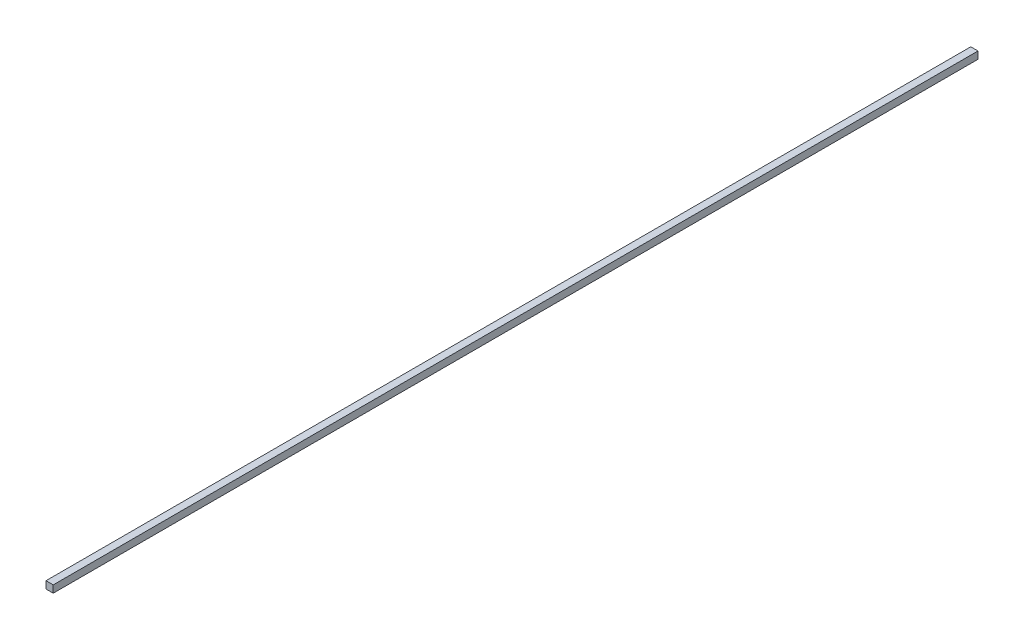
SolidWorks part; units mm, degrees
ref_plane "Front Plane" through (0, 0, 0) normal (0, 0, 1) x (1, 0, 0)
ref_plane "Top Plane" through (0, 0, 0) normal (0, 1, 0) x (1, 0, 0)
ref_plane "Right Plane" through (0, 0, 0) normal (1, 0, 0) x (0, 0, -1)
sketch "Sketch1" plane through (0, 0, 0) normal (0, 0, 1) x (1, 0, 0)
  line L0 (-1.1906, 1.1906) -> (1.1906, -1.1906) construction
  line L1 (-1.1906, 1.1906) -> (1.1906, 1.1906)
  line L2 (-1.1906, 1.1906) -> (-1.1906, -1.1906)
  line L3 (-1.1906, -1.1906) -> (1.1906, -1.1906)
  line L4 (1.1906, 1.1906) -> (1.1906, -1.1906)
  dimension "D1" = 2.3813
  dimension "D2" = 2.3813
extrude "Extrude1" add sketch "Sketch1" against normal blind 304.8
